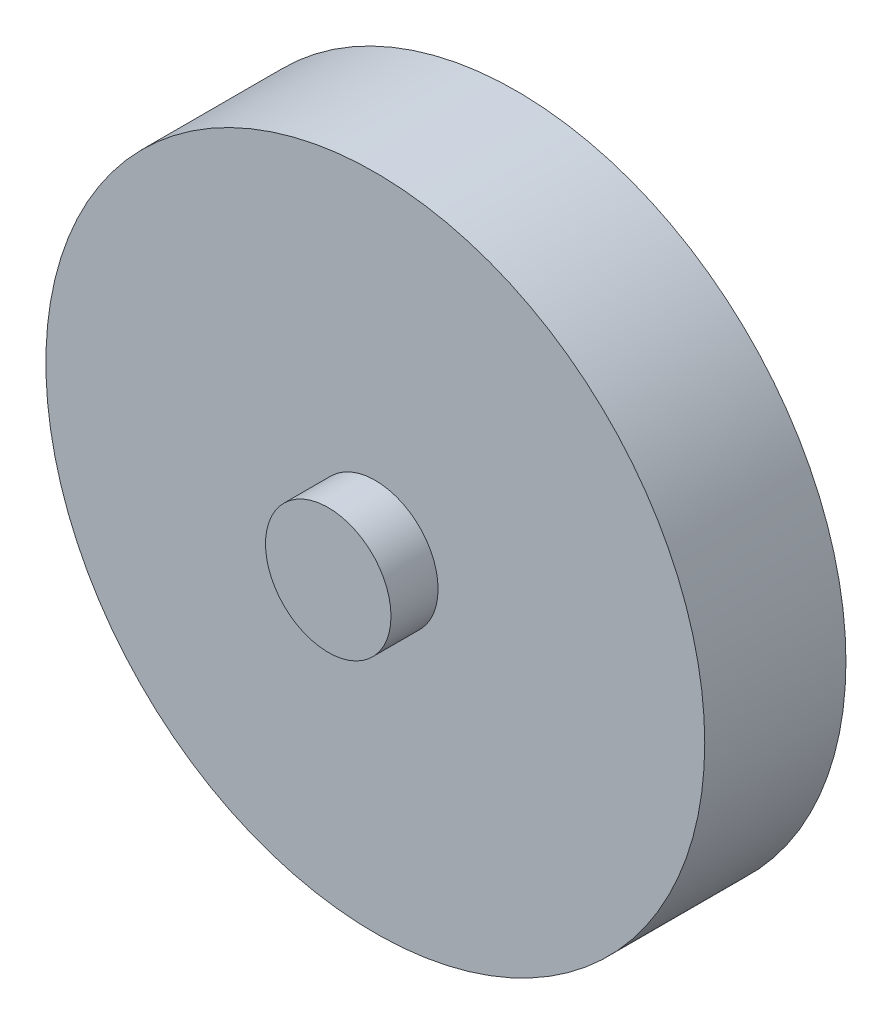
SolidWorks part; units mm, degrees
ref_plane "前视基准面" through (0, 0, 0) normal (0, 0, 1) x (1, 0, 0)
ref_plane "上视基准面" through (0, 0, 0) normal (0, 1, 0) x (1, 0, 0)
ref_plane "右视基准面" through (0, 0, 0) normal (1, 0, 0) x (0, 0, -1)
other "Configuration Table"
sketch "草图1" plane through (0, 0, 0) normal (0, 0, 1) x (1, 0, 0)
  circle A0 centre (0, 0) radius 8
extrude "凸台-拉伸1" add sketch "草图1" along normal blind 24
sketch "草图2" plane through (0, 0, 0) normal (0, 0, 1) x (1, 0, 0)
  circle A0 centre (0, 0) radius 42
extrude "凸台-拉伸2" add sketch "草图2" along normal blind 18
sketch "草图3" plane through (0, 0, 18) normal (0, 0, 1) x (1, 0, 0)
  line L0 (37.3016, 3.8521) -> (37.3889, 3.8612)
  line L1 (37.3889, 3.8612) -> (37.461, 3.8716)
  line L2 (37.461, 3.8716) -> (37.6754, 3.9151)
  line L3 (37.6754, 3.9151) -> (38.0276, 4.009)
  line L4 (38.0276, 4.009) -> (38.5116, 4.1707)
  line L5 (38.5116, 4.1707) -> (39.1199, 4.4167)
  line L6 (39.1199, 4.4167) -> (39.8432, 4.763)
  line L7 (39.8432, 4.763) -> (40.671, 4.763)
  line L8 (40.671, 4.763) -> (41.5954, 5.8158)
  line L9 (41.5954, 5.8158) -> (40.671, 4.763)
  line L10 (40.671, 4.763) -> (40.671, 4.009)
  line L11 (40.671, 4.009) -> (41.5954, 2.0165)
  line L12 (41.5954, 2.0165) -> (41.5954, 0)
  line L13 (41.5954, 0) -> (41.5954, 1.0083)
  line L14 (41.5954, 1.0083) -> (40.671, 1.0083)
  line L15 (40.671, 1.0083) -> (39.1199, 1.0083)
  line L16 (39.1199, 1.0083) -> (39.1199, 2.0165)
  line L17 (39.1199, 2.0165) -> (37.461, 2.0165)
  line L18 (37.461, 2.0165) -> (37.824, 2.0269)
  line L19 (37.824, 2.0269) -> (37.461, 2.0165)
  line L20 (37.461, 2.0165) -> (37.5326, 2.0353)
  line L21 (37.5326, 2.0353) -> (37.461, 2.0165)
  line L22 (37.461, 2.0165) -> (37.5326, 2.0353)
  line L23 (37.5326, 2.0353) -> (37.5326, 2.9422)
  line L24 (37.5326, 2.9422) -> (37.3016, 3.8521)
  circle A0 centre (0, 0) radius 42 construction
